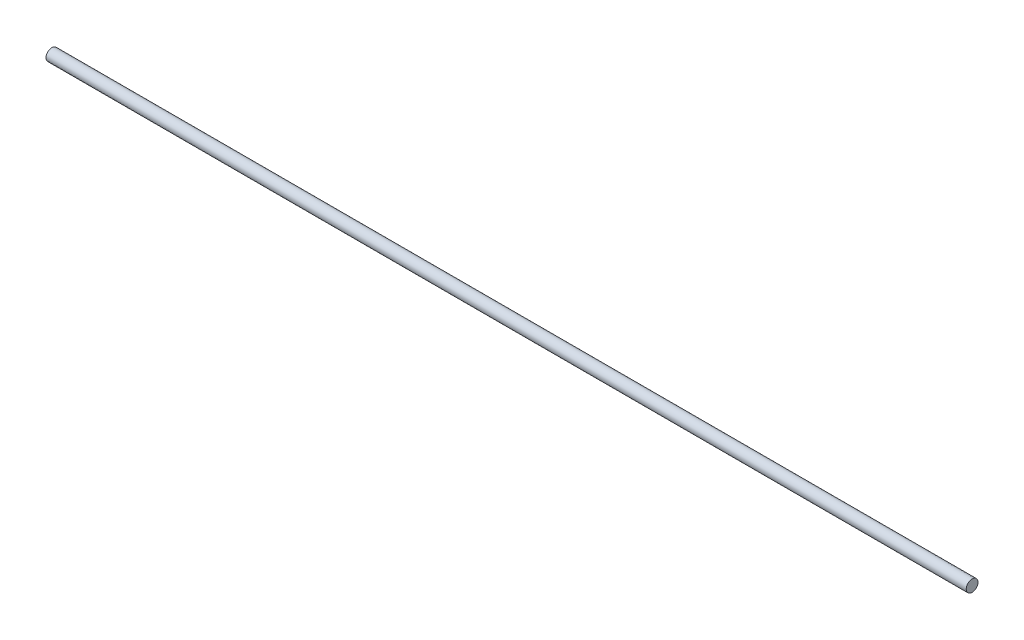
SolidWorks part; units mm, degrees
ref_plane "Front Plane" through (0, 0, 0) normal (0, 0, 1) x (1, 0, 0)
ref_plane "Top Plane" through (0, 0, 0) normal (0, 1, 0) x (1, 0, 0)
ref_plane "Right Plane" through (0, 0, 0) normal (1, 0, 0) x (0, 0, -1)
sketch "Sketch1" plane through (0, 0, 0) normal (1, 0, 0) x (0, 0, -1)
  circle A0 centre (0, 0) radius 1.4
  dimension "D1" = 2.8
extrude "Boss-Extrude1" add sketch "Sketch1" along normal blind 185 and the other way blind 34
